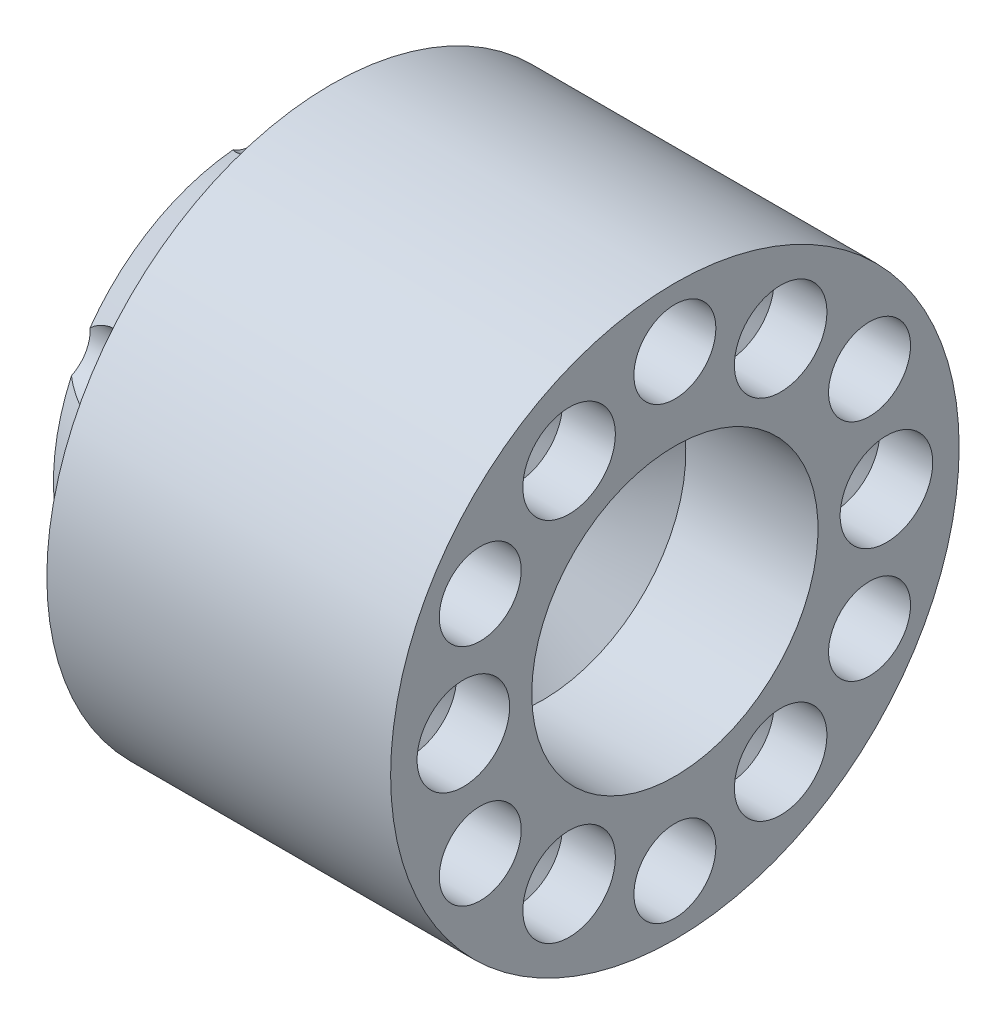
SolidWorks part; units mm, degrees
material "2018 Alloy"
ref_plane "Front Plane" through (0, 0, 0) normal (0, 0, 1) x (1, 0, 0)
ref_plane "Top Plane" through (0, 0, 0) normal (0, 1, 0) x (1, 0, 0)
ref_plane "Right Plane" through (0, 0, 0) normal (1, 0, 0) x (0, 0, -1)
sketch "Sketch1" plane through (0, 0, 0) normal (0, 0, 1) x (1, 0, 0)
  line L2 (6, 18.5) -> (0, 15)
  line L4 (0, 8.2675) -> (0, 0) construction
  line L5 (32, 0) -> (32, 10.825) construction
  line L7 (0, 0) -> (32, 0) construction
  line L13 (32, 10.825) -> (22, 10.825)
  line L14 (22, 10.825) -> (17.675, 6.5)
  line L15 (17.675, 6.5) -> (0, 8.2675)
  line L16 (6, 18.5) -> (6, 21.5)
  line L17 (6, 21.5) -> (32, 21.5)
  line L18 (0, 15) -> (0, 8.2675)
  line L26 (32, 21.5) -> (32, 10.825)
  line L27 (17.675, 6.5) -> (7.675, 6.5) construction
  line L28 (7.675, 6.5) -> (7.675, 7.5) construction
  dimension "D4" = 32
  dimension "D5" = 26
  dimension "D6" = 10
  dimension "D8" = 21.65
  dimension "D9" = 45
  dimension "D10" = 13
  dimension "D13" = 6
  dimension "D14" = 37
  dimension "D15" = 30
  dimension "D16" = 43
  dimension "D17" = 59.744
  dimension "D19" = 17.675
  dimension "D20" = 10
  dimension "D27" = 1
  dimension "D28" = 5.711
  dimension "D29" = 16.535
  dimension "D31" = 4.325
revolve "Revolve1" add sketch "Sketch1" angle 360 about L7
sketch "Sketch11" plane through (32, 0, 0) normal (1, 0, 0) x (0, 0, -1)
  line L0 (0, 0) -> (0, -17) construction
  circle A0 centre (0, 0) radius 17 construction
  circle A1 centre (0, -17) radius 3.1
  circle A2 centre (-14.7224, -8.5) radius 3.1
  circle A3 centre (-14.7224, 8.5) radius 3.1
  circle A4 centre (0, 17) radius 3.1
  circle A5 centre (14.7224, 8.5) radius 3.1
  circle A6 centre (14.7224, -8.5) radius 3.1
  dimension "D1" = 34
  dimension "D2" = 6.2
extrude "Extrude1" cut sketch "Sketch11" against normal blind 12
sketch "Sketch12" plane through (20, 0, 0) normal (1, 0, 0) x (0, 0, -1)
  circle A0 centre (0, -17) radius 3
  circle A1 centre (-14.7224, -8.5) radius 3
  circle A2 centre (-14.7224, 8.5) radius 3
  circle A3 centre (0, 17) radius 3
  circle A4 centre (14.7224, 8.5) radius 3
  circle A5 centre (14.7224, -8.5) radius 3
  dimension "D1" = 6
hole_wizard "M6 Tapped Hole1" positions "3DSketch1" profile "Sketch13" tap size "M6" standard "DIN"
sketch3d "3DSketch1"
  point P0 (20, -17, 0)
  point P3 (20, -8.5, 14.7224)
  point P6 (20, 8.5, 14.7224)
  point P9 (20, 17, 0)
  point P12 (20, 8.5, -14.7224)
  point P15 (20, -8.5, -14.7224)
sketch "Sketch13" plane through (20, -17, 0) normal (0, 1, 0) x (0, 0, -1)
  line L0 (0, 0) -> (0, 36.5022)
  line L1 (0, 36.5022) -> (2.5, 35)
  line L2 (2.5, 35) -> (2.5, 0)
  line L5 (2.5, 0) -> (0, 0)
  line L10 (0, 36.5022) -> (-2.5, 35) construction
  line L11 (0, -6.35) -> (0, 107.95) construction
  dimension "Tap Drill Dia." = 5
  dimension "Tap Drill Depth" = 35
  dimension "Drill Angle" = 118
cosmetic thread "Hole Thread3"
cosmetic thread "Hole Thread4"
cosmetic thread "Hole Thread5"
cosmetic thread "Hole Thread6"
cosmetic thread "Hole Thread7"
cosmetic thread "Hole Thread8"
sketch "Sketch14" plane through (32, 0, 0) normal (1, 0, 0) x (0, 0, -1)
  line L0 (0, -16) -> (0, 0) construction
  line L1 (0, 0) -> (8, -13.8564) construction
  circle A0 centre (0, 0) radius 16 construction
  circle A1 centre (8, -13.8564) radius 3.5
  circle A2 centre (-8, -13.8564) radius 3.5
  circle A3 centre (-16, 0) radius 3.5
  circle A4 centre (-8, 13.8564) radius 3.5
  circle A5 centre (8, 13.8564) radius 3.5
  circle A6 centre (16, 0) radius 3.5
  dimension "D1" = 32
  dimension "D3" = 7
  dimension "D2" = 30
hole_wizard "Ø7.0 (7) Diameter Hole1" positions "3DSketch2" profile "Sketch15" hole size "Ø7.0" standard "DIN"
sketch3d "3DSketch2"
  point P0 (32, -13.8564, -8)
  point P3 (32, -13.8564, 8)
  point P6 (32, 0, 16)
  point P9 (32, 13.8564, 8)
  point P12 (32, 13.8564, -8)
  point P15 (32, 0, -16)
sketch "Sketch15" plane through (32, -13.8564, -8) normal (0, 1, 0) x (0, 0, -1)
  line L0 (0, 0) -> (0, 6.103)
  line L1 (0, 6.103) -> (3.5, 4)
  line L2 (3.5, 4) -> (3.5, 0)
  line L5 (3.5, 0) -> (0, 0)
  line L10 (0, 6.103) -> (-3.5, 4) construction
  line L11 (0, -6.35) -> (0, 107.95) construction
  dimension "Hole Dia." = 7
  dimension "Hole Depth" = 4
  dimension "Drill Angle" = 118
sketch "Sketch17" plane through (0, 0, 0) normal (0, 0, 1) x (1, 0, 0)
  line L0 (0, 0) -> (0, 33.2506)
sketch "Sketch18" plane through (0, 0, 0) normal (0, 0, 1) x (1, 0, 0)
  line L0 (20.5706, 5.306) -> (-1.0846, 7.4715)
  line L1 (-1.0846, 7.4715) -> (-0.7861, 10.4566)
  line L2 (-0.7861, 10.4566) -> (20.8691, 8.2911)
  line L3 (20.8691, 8.2911) -> (20.5706, 5.306)
  line L4 (17.675, 6.5) -> (0, 8.2675) construction
  dimension "D1" = 2.1
  dimension "D2" = 3
  dimension "D3" = 1
  dimension "D4" = 3
extrude "Extrude3" cut sketch "Sketch18" against normal mid plane 7
